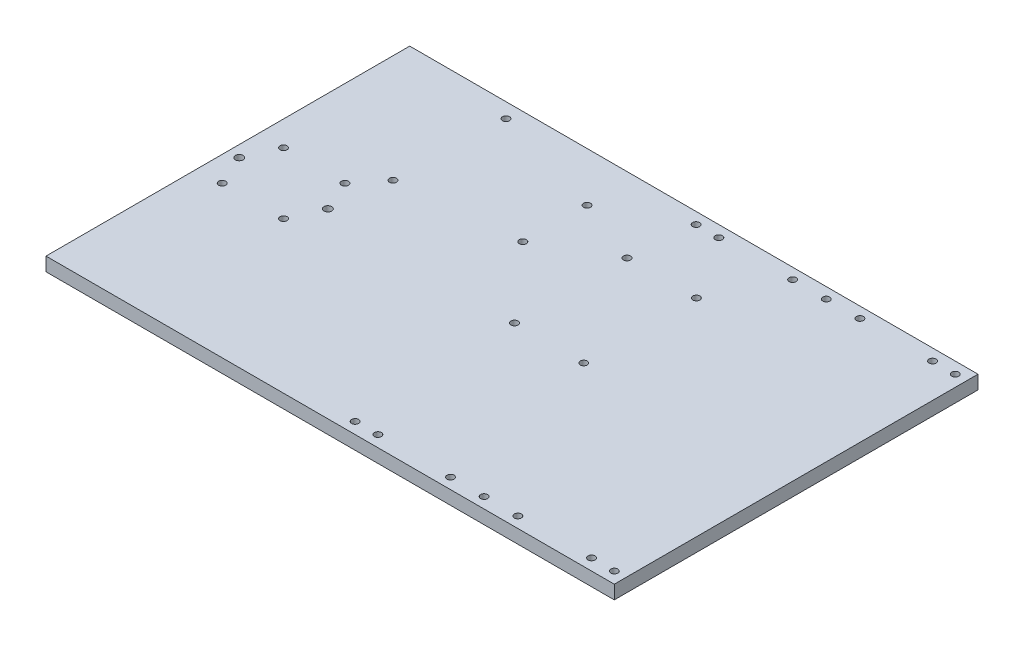
SolidWorks part; units mm, degrees
ref_plane "Front Plane" through (0, 0, 0) normal (0, 0, 1) x (1, 0, 0)
ref_plane "Top Plane" through (0, 0, 0) normal (0, 1, 0) x (1, 0, 0)
ref_plane "Right Plane" through (0, 0, 0) normal (1, 0, 0) x (0, 0, -1)
sketch "Sketch1" plane through (0, 0, 0) normal (0, 1, 0) x (1, 0, 0)
  line L1 (-125, -80) -> (125, -80)
  line L2 (-125, -80) -> (-125, 80)
  line L3 (-125, 80) -> (125, 80)
  line L4 (125, -80) -> (125, 80)
  line L5 (-125, -80) -> (125, 80) construction
  line L6 (-125, 80) -> (125, -80) construction
  point P0 (0, 0)
  dimension "D1" = 160
  dimension "D2" = 250
extrude "Boss-Extrude1" add sketch "Sketch1" along normal blind 6
hole_wizard "M3 Clearance Hole1" positions "Sketch2" profile "Sketch3" hole size "M3" standard "ISO" end condition through all
sketch "Sketch2" plane through (0, 6, 0) normal (0, 1, 0) x (1, 0, 0)
  point P23 (6, -75)
  point P25 (16, -75)
  point P27 (110, -75)
  point P29 (120, -75)
  point P50 (120, 75)
  point P53 (110, 75)
  point P56 (16, 75)
  point P59 (6, 75)
sketch "Sketch3" plane through (6, 6, 75) normal (1, 0, 0) x (0, 0, 1)
  line L0 (0, 0) -> (0, 6)
  line L1 (0, 6) -> (1.55, 6)
  line L2 (1.55, 6) -> (1.55, 0)
  line L5 (1.55, 0) -> (0, 0)
  line L11 (0, -6.35) -> (0, 107.95) construction
  dimension "Thru Hole Dia." = 3.1
  dimension "Thru Hole Depth" = 6
hole_wizard "M3 Clearance Hole2" positions "Sketch4" profile "Sketch5" hole size "M3" standard "ISO" end condition through all
sketch "Sketch4" plane through (0, 6, 0) normal (0, 1, 0) x (1, 0, 0)
  circle A0 centre (63, -75.25) radius 1.5 construction
  circle A1 centre (48.2, -75.25) radius 1.5 construction
  point P28 (48.2, 75.25)
  point P31 (63, 75.25)
  point P34 (77.8, 75.25)
  point P37 (48.2, -75.25)
  point P40 (63, -75.25)
  point P43 (77.8, -75.25)
  point P48 (0, 0)
  point P51 (0, 0)
  point P54 (0, 0)
  point P59 (0, 0)
sketch "Sketch5" plane through (48.2, 6, -75.25) normal (1, 0, 0) x (0, 0, 1)
  line L0 (0, 0) -> (0, 6)
  line L1 (0, 6) -> (1.55, 6)
  line L2 (1.55, 6) -> (1.55, 0)
  line L5 (1.55, 0) -> (0, 0)
  line L11 (0, -6.35) -> (0, 107.95) construction
  dimension "Thru Hole Dia." = 3.1
  dimension "Thru Hole Depth" = 6
hole_wizard "M3 Clearance Hole3" positions "Sketch6" profile "Sketch7" hole size "M3" standard "ISO" end condition through all
sketch "Sketch6" plane through (0, 6, 0) normal (0, 1, 0) x (1, 0, 0)
  circle A1 centre (-114, -13.5) radius 1.55 construction
  circle A2 centre (-87, -13.5) radius 1.55 construction
  point P0 (-114, -13.5)
  point P3 (-87, -13.5)
  point P6 (-87, 13.5)
  point P9 (-114, 13.5)
  point P12 (0, 0)
  point P15 (0, 0)
  point P18 (0, 0)
sketch "Sketch7" plane through (-114, 6, 13.5) normal (1, 0, 0) x (0, 0, 1)
  line L0 (0, 0) -> (0, 6)
  line L1 (0, 6) -> (1.55, 6)
  line L2 (1.55, 6) -> (1.55, 0)
  line L5 (1.55, 0) -> (0, 0)
  line L11 (0, -6.35) -> (0, 107.95) construction
  dimension "Thru Hole Dia." = 3.1
  dimension "Thru Hole Depth" = 6
hole_wizard "M3 Clearance Hole4" positions "Sketch8" profile "Sketch9" hole size "M3" standard "ISO" end condition through all
sketch "Sketch8" plane through (0, 6, 0) normal (0, 1, 0) x (1, 0, 0)
  arc A1 (-77.56, 23.609) -> (-77.56, 26.809) centre (-77.56, 25.209) ccw construction
  point P0 (3.54, -2.46)
  point P3 (34.02, -2.46)
  point P6 (34.02, 47.07)
  point P9 (3.54, 47.07)
  point P12 (-77.56, 25.209)
  point P17 (-25.59, 30.359)
  point P27 (-25.36, 58.359)
  point P30 (-76.16, 73.509)
sketch "Sketch9" plane through (3.54, 6, 2.46) normal (1, 0, 0) x (0, 0, 1)
  line L0 (0, 0) -> (0, 6)
  line L1 (0, 6) -> (1.55, 6)
  line L2 (1.55, 6) -> (1.55, 0)
  line L5 (1.55, 0) -> (0, 0)
  line L11 (0, -6.35) -> (0, 107.95) construction
  dimension "Thru Hole Dia." = 3.1
  dimension "Thru Hole Depth" = 6
hole_wizard "M3 Clearance Hole5" positions "Sketch10" profile "Sketch11" hole size "M3" standard "ISO" end condition through all
sketch "Sketch10" plane through (0, 0, 0) normal (0, -1, 0) x (-1, 0, 0)
  point P0 (81, 0)
  point P3 (120, 0)
sketch "Sketch11" plane through (-81, 0, 0) normal (1, 0, 0) x (0, 0, -1)
  line L0 (0, 0) -> (0, 6)
  line L1 (0, 6) -> (1.7, 6)
  line L2 (1.7, 6) -> (1.7, 0)
  line L5 (1.7, 0) -> (0, 0)
  line L11 (0, -6.35) -> (0, 107.95) construction
  dimension "Thru Hole Dia." = 3.4
  dimension "Thru Hole Depth" = 6
